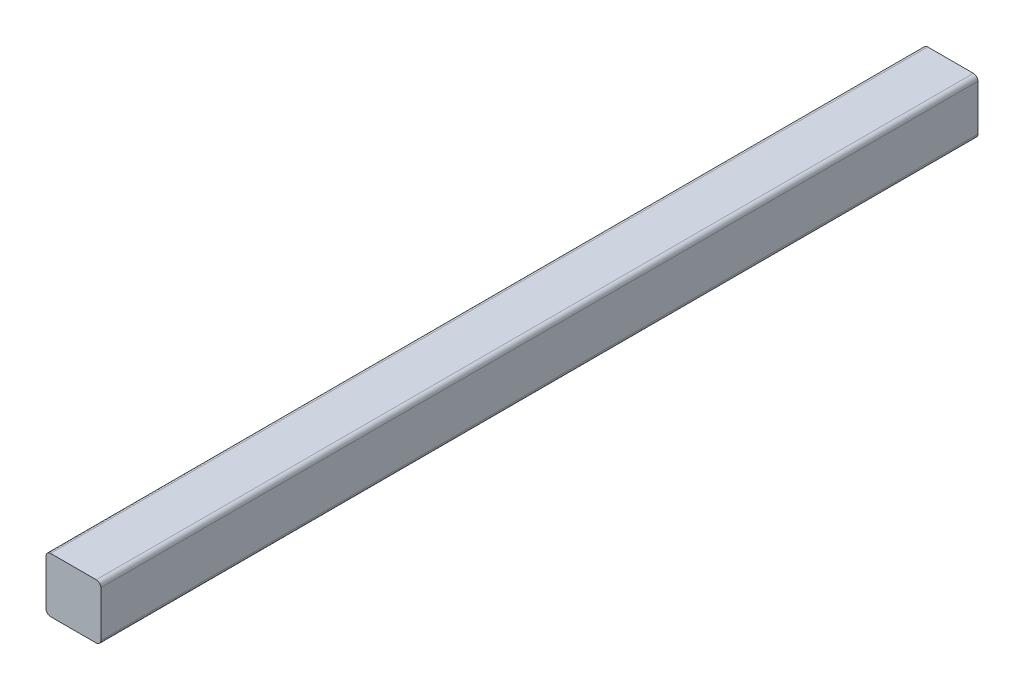
SolidWorks part; units mm, degrees
ref_plane "Front Plane" through (0, 0, 0) normal (0, 0, 1) x (1, 0, 0)
ref_plane "Top Plane" through (0, 0, 0) normal (0, 1, 0) x (1, 0, 0)
ref_plane "Right Plane" through (0, 0, 0) normal (1, 0, 0) x (0, 0, -1)
sketch "Sketch1" plane through (0, 0, 0) normal (0, 0, 1) x (1, 0, 0)
  line L1 (-19.05, -19.05) -> (19.05, -19.05)
  line L2 (-19.05, -19.05) -> (-19.05, 19.05)
  line L3 (-19.05, 19.05) -> (19.05, 19.05)
  line L4 (19.05, -19.05) -> (19.05, 19.05)
  line L5 (-19.05, -19.05) -> (19.05, 19.05) construction
  line L6 (-19.05, 19.05) -> (19.05, -19.05) construction
  point P0 (0, 0)
  dimension "D1" = 38.1
  dimension "D2" = 38.1
extrude "Boss-Extrude1" add sketch "Sketch1" along normal blind 609.6
fillet "Fillet1" radius 3.175 4 edges at (-19.05, 19.05, 304.8) (-19.05, -19.05, 304.8) (19.05, -19.05, 304.8) (19.05, 19.05, 304.8)
